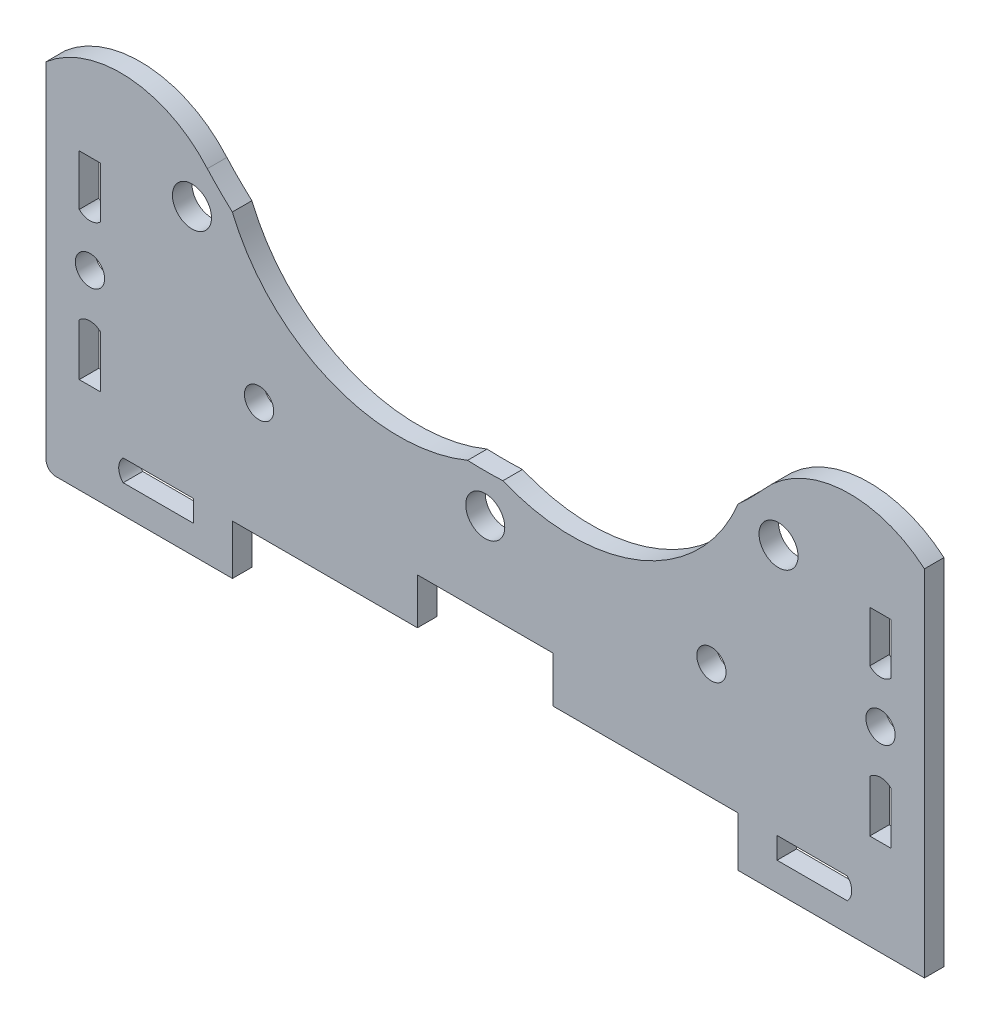
SolidWorks part; units mm, degrees
ref_plane "前视基准面" through (0, 0, 0) normal (0, 0, 1) x (1, 0, 0)
ref_plane "上视基准面" through (0, 0, 0) normal (0, 1, 0) x (1, 0, 0)
ref_plane "右视基准面" through (0, 0, 0) normal (1, 0, 0) x (0, 0, -1)
sketch "草图3" plane through (0, 0, 0) normal (0, 0, 1) x (1, 0, 0)
  line L0 (-37, -1.9902) -> (-37, -2.0902) construction
  line L5 (-37, 0.0098) -> (-30, 0.0098) construction
  line L6 (-37, 0.0098) -> (-37, -1.9902) construction
  line L7 (-37, -1.9902) -> (-30, -1.9902) construction
  line L8 (-30, 0.0098) -> (-30, -1.9902) construction
  line L9 (-37, -2.0902) -> (-37.1, -2.0902) construction
  line L12 (-41.6, 19.9098) -> (-41.6, 10.1098) construction
  line L19 (-37.1, -2.0902) -> (-29.9, -2.0902)
  line L21 (-37.1, 0.1098) -> (-29.9, 0.1098)
  line L22 (-29.9, -2.0902) -> (-29.9, 0.1098)
  line L111 (-40.5, 20.0098) -> (-40.5, 25.0098) construction
  line L112 (-41.6, 25.1098) -> (-39.4, 25.1098)
  line L113 (-41.6, 25.1098) -> (-41.6, 19.9098)
  line L115 (-39.4, 25.1098) -> (-39.4, 19.9098)
  line L116 (-41.6, 25.1098) -> (-39.4, 19.9098) construction
  line L117 (-41.6, 19.9098) -> (-39.4, 25.1098) construction
  line L119 (-39.4, 10.1098) -> (-39.4, 4.8098)
  line L120 (-39.4, 4.8098) -> (-41.6, 4.8098)
  line L121 (-41.6, 4.8098) -> (-41.6, 10.1098)
  line L122 (0, 10.5098) -> (0, 4.8098) construction
  line L124 (37.1, 0.1098) -> (29.9, 0.1098)
  line L136 (37.1, -2.0902) -> (29.9, -2.0902)
  line L147 (30, 0.0098) -> (30, -1.9902) construction
  line L148 (29.9, -2.0902) -> (29.9, 0.1098)
  line L149 (41.6, 19.9098) -> (39.4, 25.1098) construction
  line L150 (41.6, 25.1098) -> (39.4, 19.9098) construction
  line L151 (40.5, 20.0098) -> (40.5, 25.0098) construction
  line L152 (41.6, 19.9098) -> (41.6, 10.1098) construction
  line L153 (37, -2.0902) -> (37.1, -2.0902) construction
  line L154 (37, 0.0098) -> (37, -1.9902) construction
  line L155 (37, -1.9902) -> (37, -2.0902) construction
  line L157 (41.6, 4.8098) -> (41.6, 10.1098)
  line L158 (39.4, 4.8098) -> (41.6, 4.8098)
  line L159 (39.4, 10.1098) -> (39.4, 4.8098)
  line L160 (39.4, 25.1098) -> (39.4, 19.9098)
  line L162 (41.6, 25.1098) -> (41.6, 19.9098)
  line L163 (41.6, 25.1098) -> (39.4, 25.1098)
  line L171 (-25.9, -3.9902) -> (-25.9, 0.1098)
  line L172 (-25.9, 0.1098) -> (-15.9, 0.1098)
  line L180 (0, 10.5098) -> (0, 13.5) construction
  line L181 (-15.9, 0.1098) -> (-6.949, 0.1098)
  line L182 (-6.949, 0.1098) -> (-6.949, 4.8098)
  line L183 (-6.949, 4.8098) -> (6.949, 4.8098)
  line L184 (6.949, 0.1098) -> (6.949, 4.8098)
  line L185 (15.9, 0.1098) -> (6.949, 0.1098)
  line L186 (25.9, 0.1098) -> (15.9, 0.1098)
  line L187 (25.9, -3.9902) -> (25.9, 0.1098)
  line L195 (-25.9, -3.9902) -> (-25.9, -4.9902)
  line L196 (-25.9, -4.9902) -> (-45, -4.9902) construction
  line L197 (-45, -4.9902) -> (-45, -3.9902) construction
  line L198 (25.9, -3.9902) -> (25.9, -4.9902)
  line L199 (25.9, -4.9902) -> (45, -4.9902)
  line L200 (45, -4.9902) -> (45, -3.9902)
  line L201 (-45, -3.9902) -> (-45, 8.8901)
  line L203 (45, 31.3171) -> (45, 21.1286)
  line L204 (45, 8.8901) -> (45, -3.9902)
  line L208 (45, 21.1286) -> (45, 8.8901)
  line L209 (40.5, 20.0098) -> (40.5, 10.1098) construction
  line L210 (-44, -4.9902) -> (-25.9, -4.9902)
  line L212 (0, 56) -> (31.4326, 27.3951) construction
  line L213 (0, 56) -> (28.5728, 24.6019) construction
  line L214 (-45, 31.3171) -> (-45, 21.1286)
  line L215 (-45, 8.8901) -> (-45, 21.1286)
  arc A13 (-41.6, 19.9098) -> (-39.4, 19.9098) centre (-40.5, 21.0098) ccw
  arc A14 (-41.6, 10.1098) -> (-39.4, 10.1098) centre (-40.5, 9.0098) cw
  arc A15 (39.4, 10.1098) -> (41.6, 10.1098) centre (40.5, 9.0098) cw
  arc A16 (39.4, 19.9098) -> (41.6, 19.9098) centre (40.5, 21.0098) ccw
  circle A17 centre (0, 13.5) radius 2
  circle A18 centre (-30.052, 25.948) radius 2
  circle A24 centre (30.052, 25.948) radius 2
  circle A25 centre (-30.052, 86.052) radius 2 [skipped]
  circle A26 centre (0, 98.5) radius 2 [skipped]
  circle A27 centre (30.052, 86.052) radius 2 [skipped]
  circle A28 centre (42.5, 56) radius 2 [skipped]
  arc A29 (37.1, 0.1098) -> (37.1, -2.0902) centre (36, -0.9902) cw
  arc A30 (-37.1, -2.0902) -> (-37.1, 0.1098) centre (-36, -0.9902) cw
  circle A31 centre (-23.1745, 11.9598) radius 1.5
  circle A32 centre (23.1745, 11.9598) radius 1.5
  circle A40 centre (40.5, 15.0598) radius 1.5
  circle A41 centre (-40.5, 15.0598) radius 1.5
  arc A43 (-25.9127, 27.5258) -> (-1.8098, 17.5426) centre (-8.8696, 34.5856) ccw
  arc A44 (1.8098, 17.5426) -> (25.9127, 27.5258) centre (8.8696, 34.5856) ccw
  arc A46 (-25.9127, 27.5258) -> (-28.4742, 30.0873) centre (0, 56) cw
  arc A47 (-1.8098, 17.5426) -> (1.8098, 17.5426) centre (0, 56) ccw
  arc A50 (-44, -4.9902) -> (-45, -3.9902) centre (-44, -3.9902) cw
  circle A51 centre (-42.5, 56) radius 2 [skipped]
  circle A52 centre (0, 56) radius 38.5 construction
  circle A53 centre (0, 56) radius 42.5 construction
  arc A54 (25.9127, 27.5258) -> (28.4742, 30.0873) centre (0, 56) ccw
  arc A55 (28.4742, 30.0873) -> (45, 31.3171) centre (37.352, 22.4393) cw
  arc A56 (-28.4742, 30.0873) -> (-45, 31.3171) centre (-37.352, 22.4393) ccw
  point P52 (40.5, 22.5098)
  point P62 (-40.5, 22.5098)
  dimension "D1" = 1
extrude "凸台-拉伸1" add sketch "草图3" along normal blind 2
